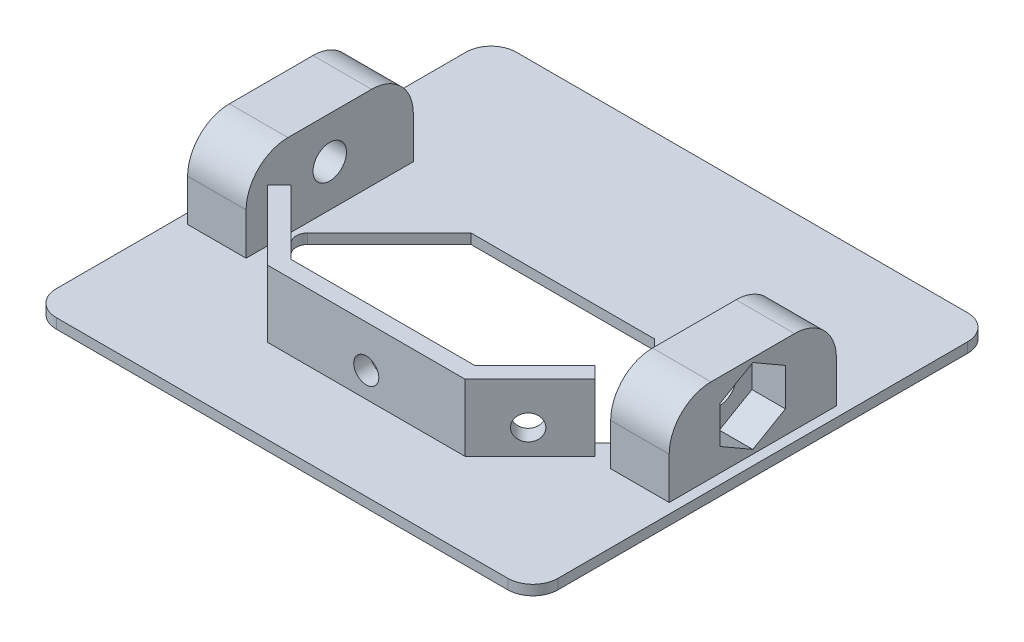
SolidWorks part; units mm, degrees
ref_plane "Plano frontal" through (0, 0, 0) normal (0, 0, 1) x (1, 0, 0)
ref_plane "Plano superior" through (0, 0, 0) normal (0, 1, 0) x (1, 0, 0)
ref_plane "Plano direito" through (0, 0, 0) normal (1, 0, 0) x (0, 0, -1)
sketch "Esboço1" plane through (0, 0, 0) normal (0, 1, 0) x (1, 0, 0)
  line L1 (-30, 27.5) -> (30, 27.5)
  line L2 (-30, 27.5) -> (-30, -27.5)
  line L3 (-30, -27.5) -> (30, -27.5)
  line L4 (30, 27.5) -> (30, -27.5)
  line L5 (-30, 27.5) -> (30, -27.5) construction
  line L6 (-30, -27.5) -> (30, 27.5) construction
  point P0 (0, 0)
  dimension "D1" = 55
  dimension "D2" = 60
extrude "Ressalto-extrusão1" add sketch "Esboço1" along normal blind 1.2
sketch "Esboço2" plane through (0, 1.2, 0) normal (0, 1, 0) x (1, 0, 0)
  line L0 (11, -15.431) -> (21.75, -4.681)
  line L1 (-11, 6.069) -> (11, 6.069)
  line L2 (-11, 6.069) -> (-11, -15.431)
  line L3 (-11, -15.431) -> (11, -15.431)
  line L4 (11, 6.069) -> (11, -15.431)
  line L5 (-11, 6.069) -> (11, -15.431) construction
  line L6 (-11, -15.431) -> (11, 6.069) construction
  line L7 (21.75, -4.681) -> (11, 6.069)
  line L8 (-11, -15.431) -> (-21.75, -4.681)
  line L9 (-21.75, -4.681) -> (-11, 6.069)
  arc A0 (-20.75, -5.681) -> (-20.75, -3.681) centre (-19.632, -4.681) cw
  arc A1 (20.75, -3.681) -> (20.75, -5.681) centre (19.632, -4.681) cw
  point P0 (0, -4.681)
  dimension "D5" = 1.5
  dimension "D8" = 1.5
  dimension "D1" = 22
  dimension "D2" = 21.5
  dimension "D3" = 1
  dimension "D4" = 1
  dimension "D6" = 1
  dimension "D7" = 1
extrude "Corte-extrusão1" cut sketch "Esboço2" against normal through all contours L4 L1 L2 L3 | A0 L8 L2 L9 | A1 L7 L4 L0
sketch "Esboço3" plane through (0, 1.2, 0) normal (0, 1, 0) x (1, 0, 0)
  line L0 (-10.9984, -17.431) -> (10.9984, -17.431)
  line L1 (-11, -15.431) -> (11, -15.431) construction
  line L2 (10.9984, -17.431) -> (11.8284, -17.431)
  line L3 (-10.9984, -17.431) -> (-11.8284, -17.431)
  line L4 (11.8284, -17.431) -> (19.6066, -9.6528)
  line L5 (-11.8284, -17.431) -> (-20.0961, -9.1633)
  line L6 (-20.0961, -9.1633) -> (-18.6819, -7.7491)
  line L7 (-11, -15.431) -> (-20.75, -5.681) construction
  line L8 (-18.6819, -7.7491) -> (-11, -15.431)
  line L9 (-11, -15.431) -> (11, -15.431)
  line L10 (11, -15.431) -> (20.75, -5.681) construction
  line L11 (19.6066, -9.6528) -> (18.1924, -8.2386)
  line L12 (18.1924, -8.2386) -> (11, -15.431)
  dimension "D1" = 2
  dimension "D2" = 0.83
  dimension "D3" = 0.83
  dimension "D4" = 11
  dimension "D5" = 2
  dimension "D6" = 2
extrude "Ressalto-extrusão2" add sketch "Esboço3" along normal blind 8
sketch "Esboço4" plane through (13.2155, 0, 13.2155) normal (-0.7071, 0, -0.7071) x (-0.7071, 0, 0.7071)
  line L0 (-7.0384, 9.2) -> (3.1332, 9.2) construction
  line L1 (3.1332, 0) -> (3.1332, 9.2) construction
  circle A0 centre (-1.3668, 4.2) radius 1.5
  dimension "D3" = 3
  dimension "D1" = 5
  dimension "D2" = 4.5
extrude "Corte-extrusão2" cut sketch "Esboço4" against normal blind 7
sketch "Esboço5" plane through (0, 0, 15.431) normal (0, 0, -1) x (-1, 0, 0)
  line L0 (-11, 9.2) -> (11, 9.2) construction
  circle A0 centre (0, 4.2) radius 1.5
  dimension "D2" = 3
  dimension "D1" = 5
extrude "Corte-extrusão3" cut sketch "Esboço5" against normal blind 7
sketch "Esboço6" plane through (-13.2155, 0, 13.2155) normal (0.7071, 0, -0.7071) x (-0.7071, 0, -0.7071)
  line L0 (-3.1332, 9.2) -> (7.7307, 9.2) construction
  line L1 (-3.1332, 0) -> (-3.1332, 9.2) construction
  circle A0 centre (1.3668, 4.2) radius 1.5
  dimension "D1" = 3
  dimension "D2" = 5
  dimension "D3" = 4.5
extrude "Corte-extrusão4" cut sketch "Esboço6" against normal blind 7
fillet "Filete1" radius 3 1 edges at (-30, 0.6, -27.5)
fillet "Filete2" radius 3 1 edges at (30, 0.6, -27.5)
fillet "Filete3" radius 3 1 edges at (30, 0.6, 27.5)
fillet "Filete4" radius 3 1 edges at (-30, 0.6, 27.5)
sketch "Esboço8" plane through (0, 1.2, 0) normal (0, 1, 0) x (1, 0, 0)
  line L0 (-30, 24.5) -> (-30, -24.5) construction
  line L1 (-21.8, 10) -> (-28.8, 10)
  line L2 (-21.8, 10) -> (-21.8, -10)
  line L3 (-21.8, -10) -> (-28.8, -10)
  line L4 (-28.8, 10) -> (-28.8, -10)
  line L5 (30, -24.5) -> (30, 24.5) construction
  line L6 (28.8, 10) -> (21.8, 10)
  line L7 (28.8, 10) -> (28.8, -10)
  line L8 (28.8, -10) -> (21.8, -10)
  line L9 (21.8, 10) -> (21.8, -10)
  point P6 (-30, 0)
  point P13 (28.8, 0)
  dimension "D1" = 20
  dimension "D2" = 10
  dimension "D3" = 7
  dimension "D4" = 1.2
  dimension "D5" = 7
  dimension "D6" = 1.2
  dimension "D7" = 10
extrude "Ressalto-extrusão3" add sketch "Esboço8" along normal blind 10
sketch "Esboço9" plane through (-28.8, 0, 0) normal (-1, 0, 0) x (0, 0, 1)
  line L1 (0, 1.7) -> (3.8971, 3.95)
  line L2 (3.8971, 3.95) -> (3.8971, 8.45)
  line L3 (3.8971, 8.45) -> (0, 10.7)
  line L4 (0, 10.7) -> (-3.8971, 8.45)
  line L5 (-3.8971, 8.45) -> (-3.8971, 3.95)
  line L6 (-3.8971, 3.95) -> (0, 1.7)
  circle A0 centre (0, 6.2) radius 3.8971 construction
  dimension "D1" = 9
extrude "Corte-extrusão6" cut sketch "Esboço9" against normal blind 4
sketch "Esboço11" plane through (-24.8, 0, 0) normal (-1, 0, 0) x (0, 0, 1)
  circle A0 centre (0, 6.2) radius 2
  dimension "D1" = 4
extrude "Corte-extrusão7" cut sketch "Esboço11" against normal blind 10
sketch "Esboço12" plane through (28.8, 0, 0) normal (1, 0, 0) x (0, 0, -1)
  line L1 (0, 1.7) -> (3.8971, 3.95)
  line L2 (3.8971, 3.95) -> (3.8971, 8.45)
  line L3 (3.8971, 8.45) -> (0, 10.7)
  line L4 (0, 10.7) -> (-3.8971, 8.45)
  line L5 (-3.8971, 8.45) -> (-3.8971, 3.95)
  line L6 (-3.8971, 3.95) -> (0, 1.7)
  circle A0 centre (0, 6.2) radius 3.8971 construction
  dimension "D1" = 9
extrude "Corte-extrusão8" cut sketch "Esboço12" against normal blind 4
sketch "Esboço13" plane through (24.8, 0, 0) normal (1, 0, 0) x (0, 0, -1)
  circle A0 centre (0, 6.2) radius 2
  dimension "D1" = 4
extrude "Corte-extrusão9" cut sketch "Esboço13" against normal blind 10
fillet "Filete5" radius 5 1 edges at (25.3, 11.2, 10)
fillet "Filete6" radius 5 1 edges at (25.3, 11.2, -10)
fillet "Filete7" radius 5 1 edges at (-25.3, 11.2, -10)
fillet "Filete9" radius 5 1 edges at (-25.3, 11.2, 10)
